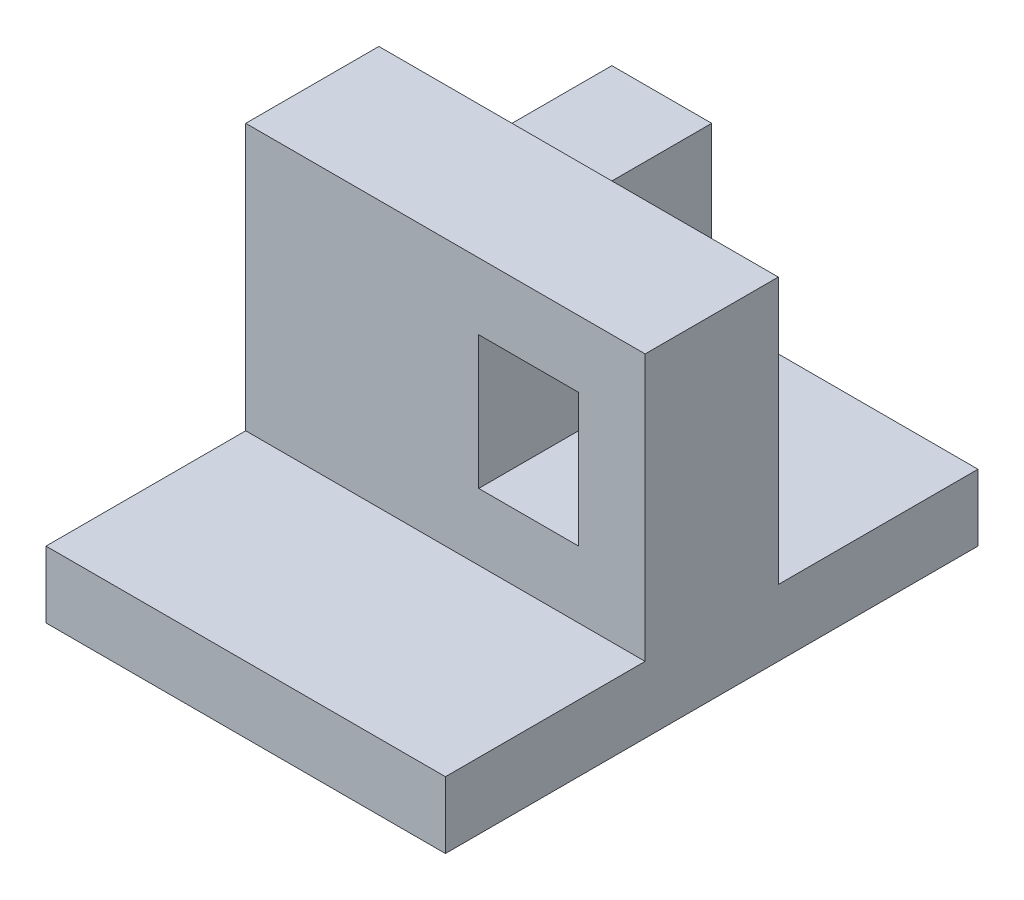
SolidWorks part; units mm, degrees
ref_plane "Plano frontal" through (0, 0, 0) normal (0, 0, 1) x (1, 0, 0)
ref_plane "Plano superior" through (0, 0, 0) normal (0, 1, 0) x (1, 0, 0)
ref_plane "Plano direito" through (0, 0, 0) normal (1, 0, 0) x (0, 0, -1)
sketch "Esboço1" plane through (0, 0, 0) normal (0, 0, 1) x (1, 0, 0)
  line L0 (0, 0) -> (-60, 0)
  line L1 (-60, 0) -> (-60, 10)
  line L2 (-60, 10) -> (0, 10)
  line L3 (0, 10) -> (0, 0)
  dimension "D1" = 60
  dimension "D2" = 10
extrude "Ressalto-extrusão1" add sketch "Esboço1" along normal blind 80
sketch "Esboço2" plane through (-60, 0, 0) normal (-1, 0, 0) x (0, 0, 1)
  line L0 (30, 10) -> (30, 50)
  line L1 (80, 10) -> (0, 10) construction
  line L2 (30, 50) -> (50, 50)
  line L3 (50, 50) -> (50, 10)
  line L4 (50, 10) -> (30, 10)
  line L5 (80, 10) -> (80, 0) construction
  dimension "D1" = 20
  dimension "D2" = 50
  dimension "D3" = 30
extrude "Ressalto-extrusão2" add sketch "Esboço2" against normal blind 60
sketch "Esboço3" plane through (0, 0, 50) normal (0, 0, 1) x (1, 0, 0)
  line L0 (-25, 40) -> (-25, 20)
  line L1 (-25, 20) -> (-10, 20)
  line L2 (-10, 20) -> (-10, 40)
  line L3 (-10, 40) -> (-25, 40)
  line L4 (-35, 40) -> (-35, 20)
  line L5 (-35, 20) -> (-50, 20)
  line L6 (-50, 20) -> (-50, 40)
  line L7 (-50, 40) -> (-35, 40)
  line L8 (0, 50) -> (-60, 50) construction
  line L9 (0, 10) -> (0, 50) construction
  dimension "D1" = 15
  dimension "D2" = 20
  dimension "D3" = 20
  dimension "D4" = 15
  dimension "D5" = 10
  dimension "D6" = 10
  dimension "D7" = 10
  dimension "D8" = 10
extrude "Corte-extrusão1" cut sketch "Esboço3" against normal blind 60
sketch "Esboço4" plane through (0, 0, 50) normal (0, 0, 1) x (1, 0, 0)
  line L0 (-50, 40) -> (-35, 40)
  line L1 (-35, 40) -> (-35, 20)
  line L2 (-35, 20) -> (-50, 20)
  line L3 (-50, 20) -> (-50, 40)
extrude "Ressalto-extrusão3" add sketch "Esboço4" against normal blind 45
